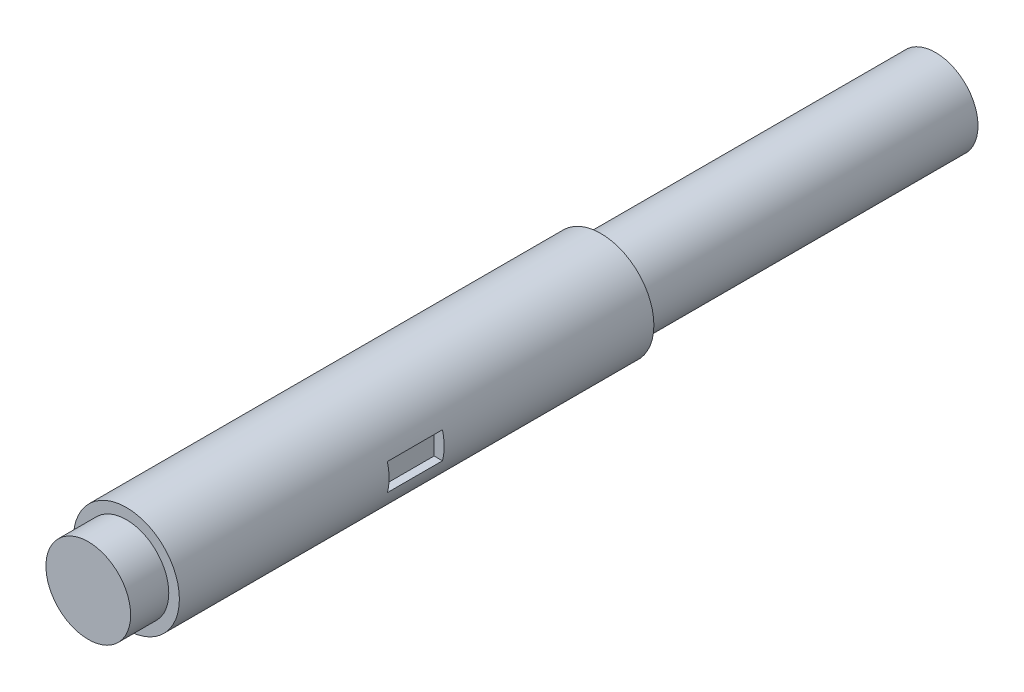
SolidWorks part; units mm, degrees
ref_plane "Front Plane" through (0, 0, 0) normal (0, 0, 1) x (1, 0, 0)
ref_plane "Top Plane" through (0, 0, 0) normal (0, 1, 0) x (1, 0, 0)
ref_plane "Right Plane" through (0, 0, 0) normal (1, 0, 0) x (0, 0, -1)
sketch "Sketch1" plane through (0, 0, 0) normal (0, 0, 1) x (1, 0, 0)
  circle A0 centre (0, 0) radius 12.5
extrude "Boss-Extrude1" add sketch "Sketch1" along normal blind 112 contours A0
sketch "Sketch2" plane through (0, 0, 112) normal (0, 0, 1) x (1, 0, 0)
  circle A0 centre (0, 0) radius 10
sketch "Sketch3" plane through (0, 0, 0) normal (0, 0, -1) x (-1, 0, 0)
  circle A0 centre (0, 0) radius 10
extrude "Boss-Extrude2" add sketch "Sketch2" along normal blind 9
extrude "Boss-Extrude3" add sketch "Sketch3" along normal blind 9
ref_plane "Plane1" through (12.5, 0, 0) normal (1, 0, 0) x (0, 0, -1)
sketch "Sketch4" plane through (12.5, 0, 0) normal (1, 0, 0) x (0, 0, -1)
  line L0 (-121, 10) -> (-121, -10) construction
  line L1 (-49.5, 3.175) -> (-62.5, 3.175)
  line L2 (-49.5, 3.175) -> (-49.5, -3.175)
  line L3 (-49.5, -3.175) -> (-62.5, -3.175)
  line L4 (-62.5, 3.175) -> (-62.5, -3.175)
  line L8 (0, 12.5) -> (-112, 12.5) construction
  dimension "D1" = 58.5
  dimension "D2" = 13
  dimension "D3" = 6.35
  dimension "D4" = 9.325
extrude "Cut-Extrude1" cut sketch "Sketch4" against normal blind 2.3813
sketch "Sketch6" plane through (0, 0, -9) normal (0, 0, -1) x (-1, 0, 0)
  circle A0 centre (0, 0) radius 10
extrude "Boss-Extrude5" add sketch "Sketch6" along normal blind 70
